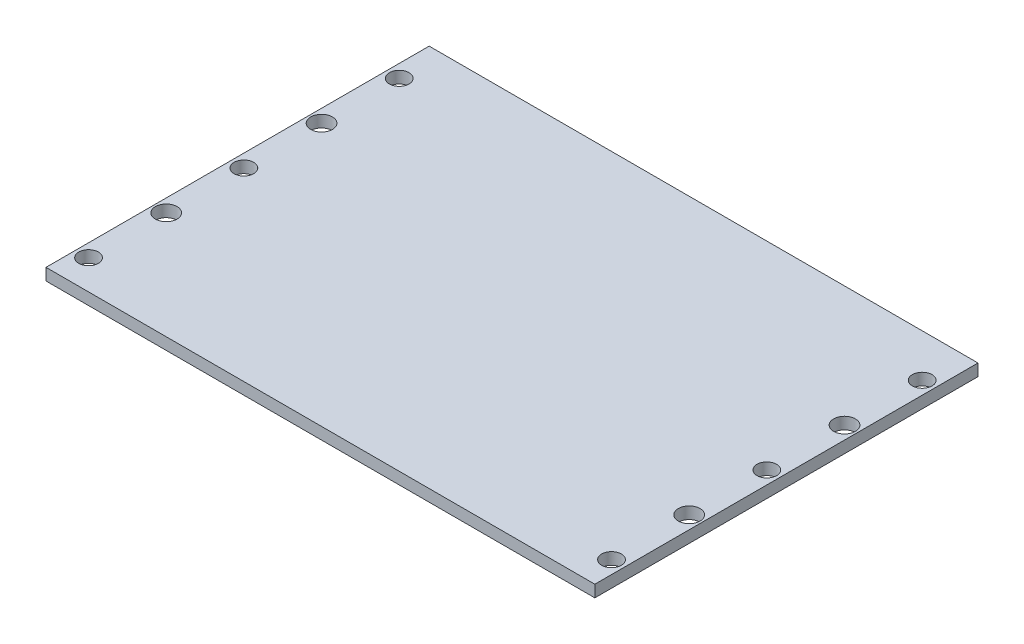
SolidWorks part; units mm, degrees
ref_plane "Front Plane" through (0, 0, 0) normal (0, 0, 1) x (1, 0, 0)
ref_plane "Top Plane" through (0, 0, 0) normal (0, 1, 0) x (1, 0, 0)
ref_plane "Right Plane" through (0, 0, 0) normal (1, 0, 0) x (0, 0, -1)
sketch "Sketch1" plane through (0, 0, 0) normal (0, 1, 0) x (1, 0, 0)
  line L1 (-3, 0) -> (103, 0)
  line L2 (-3, 0) -> (-3, 74)
  line L3 (-3, 74) -> (103, 74)
  line L4 (103, 0) -> (103, 74)
extrude "Boss-Extrude1" add sketch "Sketch1" along normal blind 2.29
ref_plane "center-of-module" through (50, 0, 0) normal (1, 0, 0) x (0, 0, -1)
sketch "Sketch2" plane through (0, 2.29, 0) normal (0, 1, 0) x (1, 0, 0)
  circle A0 centre (-0.5, 5.72) radius 1.9
  circle A1 centre (100.5, 5.72) radius 1.9
  circle A2 centre (100.5, 35.72) radius 1.9
  circle A3 centre (100.5, 65.72) radius 1.9
  circle A4 centre (-0.5, 35.72) radius 1.9
  circle A5 centre (-0.5, 65.72) radius 1.9
  circle A6 centre (-0.5, 20.72) radius 2.1
  circle A7 centre (100.5, 20.72) radius 2.1
  circle A8 centre (100.5, 50.72) radius 2.1
  circle A9 centre (-0.5, 50.72) radius 2.1
  dimension "D1" = 2
  dimension "D3" = 2
  dimension "D2" = 3
  dimension "D4" = 2
extrude "Cut-Extrude1" cut sketch "Sketch2" against normal through all
